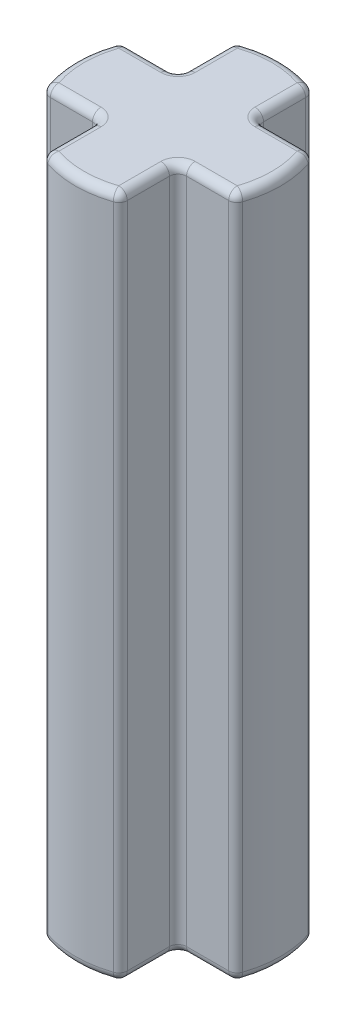
SolidWorks part; units mm, degrees
ref_plane "Front Plane" through (0, 0, 0) normal (0, 0, 1) x (1, 0, 0)
ref_plane "Top Plane" through (0, 0, 0) normal (0, 1, 0) x (1, 0, 0)
ref_plane "Right Plane" through (0, 0, 0) normal (1, 0, 0) x (0, 0, -1)
sketch "Sketch1" plane through (0, 0, 0) normal (0, 1, 0) x (1, 0, 0)
  line L0 (-0.9, -0.9) -> (-0.9, -2.2249)
  line L1 (-0.9, -0.9) -> (-2.2249, -0.9)
  line L2 (0.9, 0.9) -> (0.9, 2.2249)
  line L4 (-0.9, 2.2249) -> (-0.9, 0.9)
  line L6 (0.9, -2.2249) -> (0.9, -0.9)
  line L7 (0.9, 0.9) -> (2.2249, 0.9)
  line L9 (2.2249, -0.9) -> (0.9, -0.9)
  line L11 (-2.2249, 0.9) -> (-0.9, 0.9)
  arc A0 (-2.2249, 0.9) -> (-2.2249, -0.9) centre (0, 0) ccw
  arc A1 (-0.9, -2.2249) -> (0.9, -2.2249) centre (0, 0) ccw
  arc A2 (2.2249, -0.9) -> (2.2249, 0.9) centre (0, 0) ccw
  arc A3 (0.9, 2.2249) -> (-0.9, 2.2249) centre (0, 0) ccw
  dimension "D1" = 4.8
extrude "Boss-Extrude1" add sketch "Sketch1" along normal mid plane 16
fillet "Fillet3" radius 0.2 36 edges at (0.9, 0, 2.2249) (0.9, 0, 0.9) (2.2249, 0, 0.9) (2.2249, 0, -0.9) (0.9, 0, -0.9) (0.9, 0, -2.2249) (-2.2249, 0, -0.9) (-0.9, 0, -2.2249) (-0.9, 0, -0.9) (-0.9, 0, 2.2249) (-2.2249, 0, 0.9) (-0.9, 0, 0.9) (-1.5624, -8, 0.9) (-0.9, -8, 1.5624) (0, -8, 2.4) (0.9, -8, 1.5624) (1.5624, -8, 0.9) (2.4, -8, 0) (1.5624, -8, -0.9) (0.9, -8, -1.5624) (0, -8, -2.4) (-0.9, -8, -1.5624) (-1.5624, -8, -0.9) (-2.4, -8, 0) (-1.5624, 8, -0.9) (-0.9, 8, -1.5624) (0, 8, -2.4) (0.9, 8, -1.5624) (1.5624, 8, -0.9) (2.4, 8, 0) (1.5624, 8, 0.9) (0.9, 8, 1.5624) (0, 8, 2.4) (-0.9, 8, 1.5624) (-1.5624, 8, 0.9) (-2.4, 8, 0)
